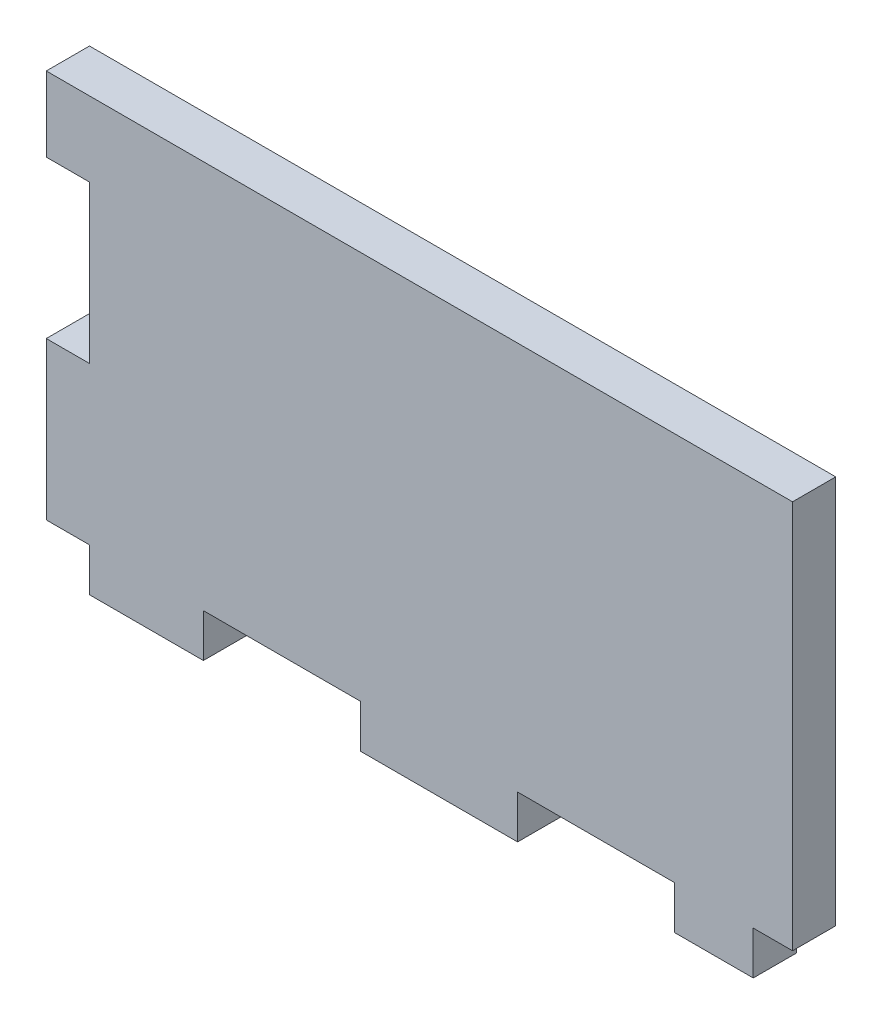
SolidWorks part; units mm, degrees
material "ﾁｰｸ材"
ref_plane "正面" through (0, 0, 0) normal (0, 0, 1) x (1, 0, 0)
ref_plane "平面" through (0, 0, 0) normal (0, 1, 0) x (1, 0, 0)
ref_plane "右側面" through (0, 0, 0) normal (1, 0, 0) x (0, 0, -1)
sketch "ｽｹｯﾁ1" plane through (0, 0, 0) normal (0, 0, 1) x (1, 0, 0)
  line L1 (47.5, 27.5) -> (-47.5, 27.5)
  line L2 (47.5, 27.5) -> (47.5, -27.5)
  line L3 (47.5, -27.5) -> (-47.5, -27.5)
  line L4 (-47.5, 27.5) -> (-47.5, -27.5)
  line L5 (47.5, 27.5) -> (-47.5, -27.5) construction
  line L6 (47.5, -27.5) -> (-47.5, 27.5) construction
  point P0 (0, 0)
  dimension "D1" = 55
  dimension "D2" = 95
extrude "ﾎﾞｽ - 押し出し1" add sketch "ｽｹｯﾁ1" along normal blind 5.5
sketch "ｽｹｯﾁ3" plane through (0, 0, 5.5) normal (0, 0, 1) x (1, 0, 0)
  line L0 (-47.5, 27.5) -> (-47.5, -27.5) construction
  line L1 (-47.5, -22) -> (-42, -22)
  line L2 (-47.5, -22) -> (-47.5, -42)
  line L3 (-47.5, -42) -> (-42, -42)
  line L4 (-42, -22) -> (-42, -42)
  line L5 (-47.5, -27.5) -> (47.5, -27.5) construction
  line L6 (-47.5, 18) -> (-47.5, -2)
  line L7 (-47.5, 18) -> (-42, 18)
  line L8 (-42, 18) -> (-42, -2)
  line L9 (-47.5, -2) -> (-42, -2)
  dimension "D1" = 5.5
  dimension "D2" = 20
  dimension "D3" = 5.5
  dimension "D4" = 2
extrude "ｶｯﾄ - 押し出し2" cut sketch "ｽｹｯﾁ3" against normal through all
sketch "ｽｹｯﾁ4" plane through (0, 0, 5.5) normal (0, 0, 1) x (1, 0, 0)
  line L0 (-42, -27.5) -> (47.5, -27.5) construction
  line L1 (-27.5, -27.5) -> (-7.5, -27.5)
  line L2 (-27.5, -27.5) -> (-27.5, -21.9959)
  line L3 (-27.5, -21.9959) -> (-7.5, -21.9959)
  line L4 (-7.5, -27.5) -> (-7.5, -21.9959)
  line L5 (-47.5, -2) -> (-47.5, -22) construction
  line L6 (12.5, -27.5) -> (12.5, -21.9959)
  line L7 (12.5, -27.5) -> (32.5, -27.5)
  line L8 (32.5, -27.5) -> (32.5, -21.9959)
  line L9 (12.5, -21.9959) -> (32.5, -21.9959)
  line L14 (47.5, -27.5) -> (47.5, 27.5) construction
  line L15 (42.5, -27.5) -> (47.5, -27.5)
  line L16 (42.5, -27.5) -> (42.5, -21.9959)
  line L17 (42.5, -21.9959) -> (47.5, -21.9959)
  line L18 (47.5, -27.5) -> (47.5, -21.9959)
  dimension "D1" = 5.5041
  dimension "D2" = 20
  dimension "D3" = 20
  dimension "D5" = 10
  dimension "D6" = 20
  dimension "D4" = 2
extrude "ｶｯﾄ - 押し出し3" cut sketch "ｽｹｯﾁ4" against normal through all
